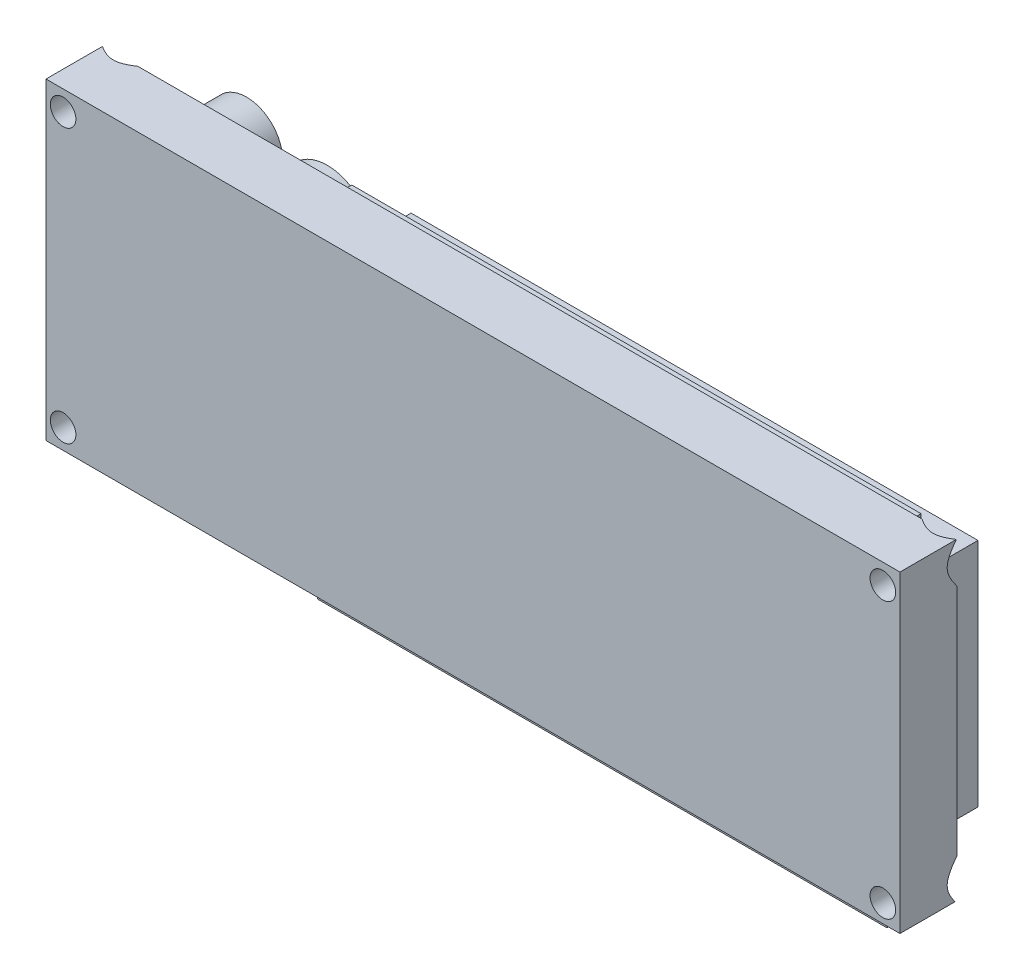
SolidWorks part; units mm, degrees
ref_plane "Front Plane" through (0, 0, 0) normal (0, 0, 1) x (1, 0, 0)
ref_plane "Top Plane" through (0, 0, 0) normal (0, 1, 0) x (1, 0, 0)
ref_plane "Right Plane" through (0, 0, 0) normal (1, 0, 0) x (0, 0, -1)
sketch "Sketch1" plane through (0, 0, 0) normal (0, 0, 1) x (1, 0, 0)
  line L1 (75, -27.5) -> (-75, -27.5)
  line L2 (75, -27.5) -> (75, 27.5)
  line L3 (75, 27.5) -> (-75, 27.5)
  line L4 (-75, -27.5) -> (-75, 27.5)
  line L5 (75, -27.5) -> (-75, 27.5) construction
  line L6 (75, 27.5) -> (-75, -27.5) construction
  point P0 (0, 0)
extrude "Boss-Extrude1" add sketch "Sketch1" along normal blind 10
hole_wizard "CSK for M4 Countersunk Flat Head Screw1" positions "Sketch2" profile "Sketch3" countersink size "M4" standard "ISO" end condition through all
sketch "Sketch2" plane through (0, 0, 0) normal (0, 0, -1) x (-1, 0, 0)
  point P0 (-72, 24)
  point P2 (-72, -24.3198)
  point P4 (72, -24)
  point P6 (72, 24)
sketch "Sketch3" plane through (72, 24, 0) normal (1, 0, 0) x (0, 1, 0)
  line L0 (0, 0) -> (0, 10)
  line L1 (0, 10) -> (2.25, 10)
  line L2 (2.25, 10) -> (2.25, 2.45)
  line L3 (2.25, 2.45) -> (4.7, 0)
  line L5 (4.7, 0) -> (0, 0)
  line L6 (-2.25, 2.45) -> (-4.7, 0) construction
  line L11 (0, -6.35) -> (0, 107.95) construction
  dimension "Thru Hole Dia." = 4.5
  dimension "Thru Hole Depth" = 10
  dimension "Near C'Sink Dia." = 9.4
  dimension "Near C'Sink Angle" = 90
sketch "Sketch4" plane through (0, 0, 0) normal (0, 0, -1) x (-1, 0, 0)
  line L1 (37.29, -37.7679) -> (-62.71, -37.7679)
  line L2 (37.29, -37.7679) -> (37.29, 22.2321)
  line L3 (37.29, 22.2321) -> (-62.71, 22.2321)
  line L4 (-62.71, -37.7679) -> (-62.71, 22.2321)
  line L5 (37.29, -37.7679) -> (-62.71, 22.2321) construction
  line L6 (37.29, 22.2321) -> (-62.71, -37.7679) construction
  point P0 (-12.71, -7.7679)
extrude "Boss-Extrude2" add sketch "Sketch4" along normal blind 6
sketch "Sketch5" plane through (0, 0, -6) normal (0, 0, -1) x (-1, 0, 0)
  line L0 (-62.71, 22.2321) -> (-62.71, -37.7679) construction
  line L1 (36.8772, 13.1652) -> (-62.71, 13.1652)
  line L2 (36.8772, 13.1652) -> (36.8772, -27.3892)
  line L3 (36.8772, -27.3892) -> (-62.71, -27.3892)
  line L4 (-62.71, 13.1652) -> (-62.71, -27.3892)
  line L5 (36.8772, 13.1652) -> (-62.71, -27.3892) construction
  line L6 (36.8772, -27.3892) -> (-62.71, 13.1652) construction
  point P0 (-12.9164, -7.112)
extrude "Boss-Extrude3" add sketch "Sketch5" along normal blind 10
sketch "Sketch6" plane through (0, 0, 0) normal (0, 0, -1) x (-1, 0, 0)
  circle A0 centre (59.7716, 16.0414) radius 6.3254
extrude "Boss-Extrude4" add sketch "Sketch6" along normal blind 10
sketch "Sketch7" plane through (0, 0, 0) normal (0, 0, -1) x (-1, 0, 0)
  line L1 (57.7679, -16.3134) -> (63.3813, -16.3134)
  line L2 (57.7679, -16.3134) -> (57.7679, -22.2536)
  line L3 (57.7679, -22.2536) -> (63.3813, -22.2536)
  line L4 (63.3813, -16.3134) -> (63.3813, -22.2536)
  line L5 (57.7679, -16.3134) -> (63.3813, -22.2536) construction
  line L6 (57.7679, -22.2536) -> (63.3813, -16.3134) construction
  circle A0 centre (60.5746, -3.7361) radius 6.761
  point P0 (60.5746, -19.2835)
extrude "Boss-Extrude5" add sketch "Sketch7" along normal blind 5
sketch "Sketch8" plane through (0, 0, -5) normal (0, 0, -1) x (-1, 0, 0)
  circle A0 centre (60.5746, -3.7361) radius 7.8253
extrude "Boss-Extrude6" add sketch "Sketch8" along normal blind 20
